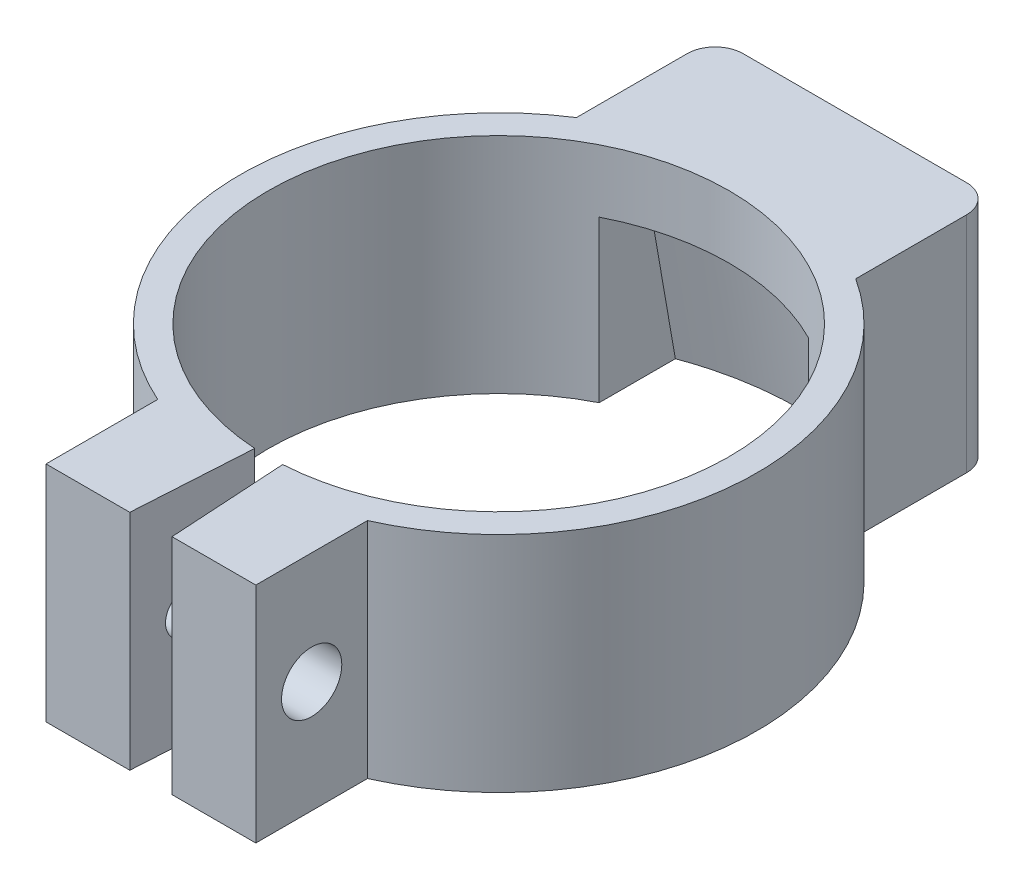
SolidWorks part; units mm, degrees
ref_plane "Front Plane" through (0, 0, 0) normal (0, 0, 1) x (1, 0, 0)
ref_plane "Top Plane" through (0, 0, 0) normal (0, 1, 0) x (1, 0, 0)
ref_plane "Right Plane" through (0, 0, 0) normal (1, 0, 0) x (0, 0, -1)
sketch "Sketch1" plane through (0, 0, 0) normal (0, 1, 0) x (1, 0, 0)
  line L0 (0, 34.5201) -> (0, -34.5201) construction
  line L1 (0, 0) -> (1.4348, -23.6302) construction
  line L2 (0, 0) -> (-1.4348, -23.6302) construction
  line L3 (1, -16.4697) -> (1.5122, -24.9061)
  line L4 (1.5122, -24.9061) -> (7.5122, -24.9061)
  line L5 (7.5122, -24.9061) -> (7.5122, -16.9061)
  line L6 (-7.5122, -24.9061) -> (-7.5122, -16.9061)
  line L7 (-1.5122, -24.9061) -> (-7.5122, -24.9061)
  line L8 (-1, -16.4697) -> (-1.5122, -24.9061)
  line L9 (-10, 25.5) -> (10, 25.5)
  line L10 (10, 25.5) -> (10, 15.5644)
  line L11 (-10, 25.5) -> (-10, 15.5644)
  circle A0 centre (0, 0) radius 16.5 construction
  arc A1 (1, -16.4697) -> (-1, -16.4697) centre (0, 0) ccw
  arc A2 (7.5122, -16.9061) -> (10, 15.5644) centre (0, 0) ccw
  arc A3 (1.1212, -18.466) -> (-1.1212, -18.466) centre (0, 0) ccw construction
  arc A4 (-10, 15.5644) -> (-7.5122, -16.9061) centre (0, 0) ccw
  point P5 (0, 0)
  point P8 (1, -16.4697)
  point P9 (1, -16.4697)
  point P10 (-1, -16.4697)
  point P11 (0, -16.5)
  point P25 (0, 18.5)
  point P29 (0, 25.5)
  dimension "D1" = 33
  dimension "D7" = 7
  dimension "D2" = 1
  dimension "D4" = 6
  dimension "D5" = 8
  dimension "D6" = 10
  dimension "D3" = 2
extrude "Boss-Extrude1" add sketch "Sketch1" along normal blind 16
sketch "Sketch2" plane through (0, 0, 0) normal (1, 0, 0) x (0, 0, -1)
  line L0 (16.5, 11.5103) -> (19.5, 11.5103) construction
  line L1 (16.5, 0) -> (16.5, 16) construction
  line L3 (19.5, 11.5103) -> (21.5, 0)
  line L4 (15.5644, 0) -> (25.5, 0) construction
  line L5 (21.5, 0) -> (16.5, 0) construction
  dimension "D1" = 3
  dimension "D2" = 5
sketch "Sketch3" plane through (0, 0, 0) normal (0, 1, 0) x (1, 0, 0)
  line L1 (0, 16.5) -> (0, 19.5) construction
  line L2 (-7.5, 20.1494) -> (-7.5, 12.3233)
  line L3 (-7.5, 12.3233) -> (7.5, 12.3233)
  line L5 (7.5, 20.1494) -> (7.5, 12.3233)
  arc A0 (7.5, 20.1494) -> (-7.5, 20.1494) centre (0, 0) ccw
  point P8 (0, 18)
  dimension "D1" = 7.5
sweep "Cut-Sweep1" cut profiles "Sketch3" path "Sketch2"
sketch "Sketch4" plane through (-7.5122, 0, 0) normal (-1, 0, 0) x (0, 0, 1)
  line L0 (16.9061, 16) -> (24.9061, 0) construction
  circle A0 centre (20.9061, 8) radius 1.5875
  dimension "D1" = 3.175
extrude "Cut-Extrude1" cut sketch "Sketch4" against normal up to next
sketch "Sketch5" plane through (7.5122, 0, 0) normal (1, 0, 0) x (0, 0, -1)
  circle A0 centre (-20.9061, 8) radius 2.159
  dimension "D1" = 4.318
extrude "Cut-Extrude2" cut sketch "Sketch5" against normal up to next
fillet "Fillet1" radius 2 2 edges at (-10, 8, -25.5) (10, 8, -25.5)
